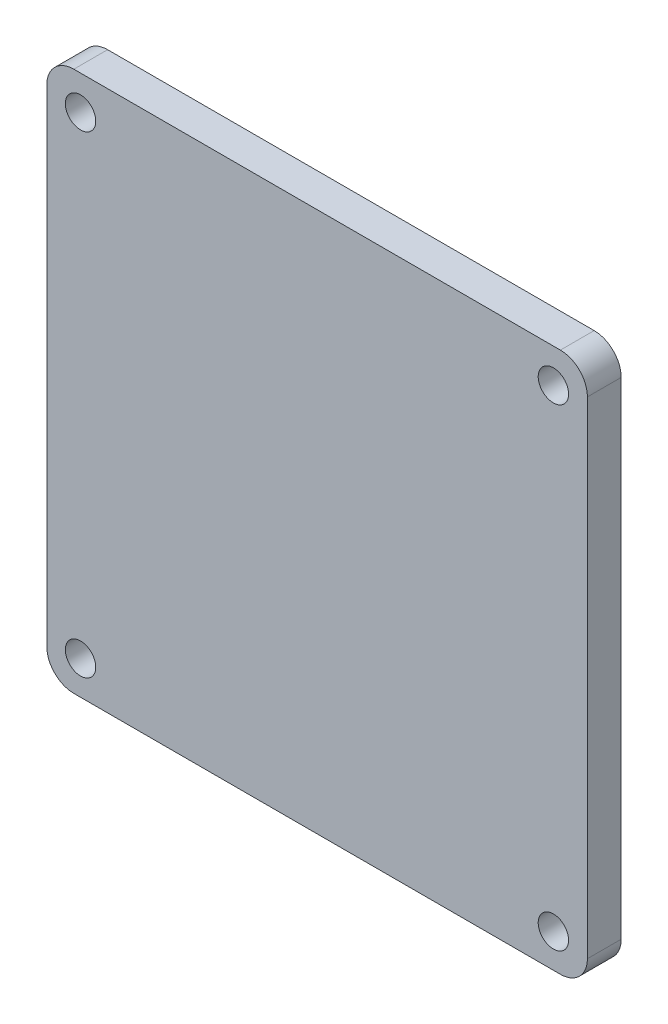
SolidWorks part; units mm, degrees
ref_plane "Plan de face" through (0, 0, 0) normal (0, 0, 1) x (1, 0, 0)
ref_plane "Plan de dessus" through (0, 0, 0) normal (0, 1, 0) x (1, 0, 0)
ref_plane "Plan de droite" through (0, 0, 0) normal (1, 0, 0) x (0, 0, -1)
sketch "Esquisse1" plane through (0, 0, 0) normal (0, 0, 1) x (1, 0, 0)
  line L1 (-36, -40) -> (36, -40)
  line L2 (-40, -36) -> (-40, 36)
  line L3 (-36, 40) -> (36, 40)
  line L4 (40, -36) -> (40, 36)
  line L5 (-40, -40) -> (40, 40) construction
  line L6 (-40, 40) -> (40, -40) construction
  arc A0 (-36, -40) -> (-40, -36) centre (-36, -36) cw
  arc A1 (36, -40) -> (40, -36) centre (36, -36) ccw
  arc A2 (40, 36) -> (36, 40) centre (36, 36) ccw
  arc A3 (-40, 36) -> (-36, 40) centre (-36, 36) cw
  point P0 (0, 0)
  dimension "D3" = 4
  dimension "D1" = 80
  dimension "D2" = 80
extrude "Boss.-Extru.1" add sketch "Esquisse1" along normal blind 5
hole_wizard "Dégagement M41" positions "Esquisse3" profile "Esquisse2" hole size "M4" standard "JIS" end condition through all
sketch "Esquisse3" plane through (0, 0, 5) normal (0, 0, 1) x (1, 0, 0)
  point P0 (-35.0076, 34.9624)
  point P2 (34.9684, 34.9624)
  point P4 (34.9684, -35.0239)
  point P6 (-35.0076, -35.0239)
sketch "Esquisse2" plane through (-35.0076, 34.9624, 5) normal (1, 0, 0) x (0, -1, 0)
  line L0 (0, 0) -> (0, 5)
  line L1 (0, 5) -> (2.25, 5)
  line L2 (2.25, 5) -> (2.25, 0)
  line L5 (2.25, 0) -> (0, 0)
  line L11 (0, -6.35) -> (0, 107.95) construction
  dimension "Diamètre du perçage jusqu'au prochain" = 4.5
  dimension "Profondeur du perçage jusqu'au prochain" = 5
